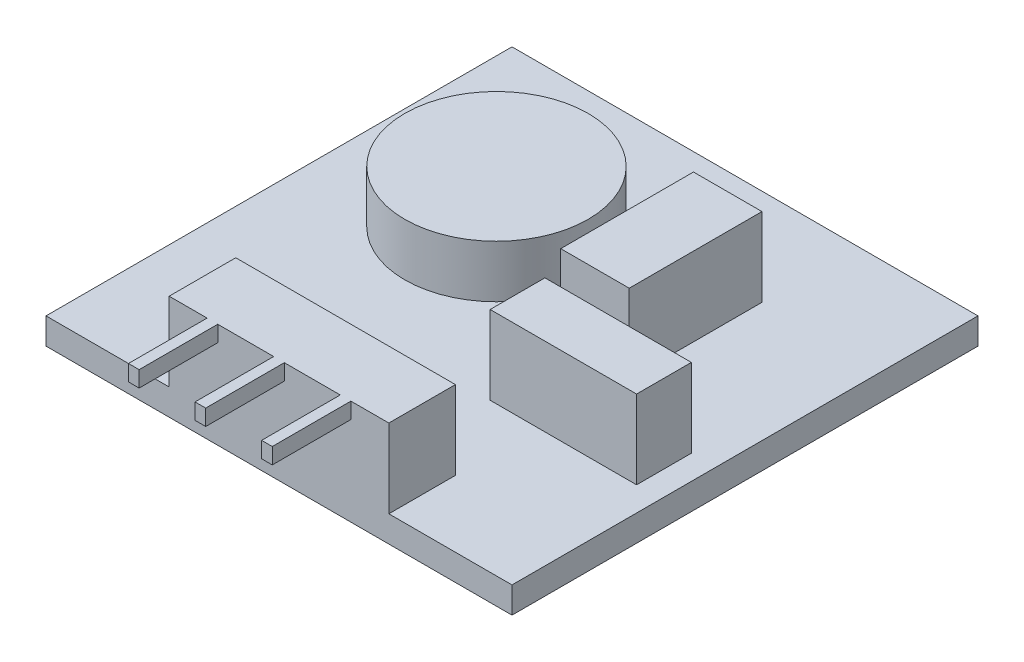
SolidWorks part; units mm, degrees
ref_plane "Front Plane" through (0, 0, 0) normal (0, 0, 1) x (1, 0, 0)
ref_plane "Top Plane" through (0, 0, 0) normal (0, 1, 0) x (1, 0, 0)
ref_plane "Right Plane" through (0, 0, 0) normal (1, 0, 0) x (0, 0, -1)
sketch "Sketch1" plane through (0, 0, 0) normal (0, 1, 0) x (1, 0, 0)
  line L1 (-8.89, -8.89) -> (8.89, -8.89)
  line L2 (-8.89, -8.89) -> (-8.89, 8.89)
  line L3 (-8.89, 8.89) -> (8.89, 8.89)
  line L4 (8.89, -8.89) -> (8.89, 8.89)
  line L5 (-8.89, -8.89) -> (8.89, 8.89) construction
  line L6 (-8.89, 8.89) -> (8.89, -8.89) construction
  point P0 (0, 0)
  dimension "D1" = 17.78
extrude "Boss-Extrude1" add sketch "Sketch1" along normal blind 1
sketch "Sketch2" plane through (0, 1, 0) normal (0, 1, 0) x (1, 0, 0)
  circle A0 centre (-3.2361, 2.6432) radius 3.5
  dimension "D1" = 7
extrude "Boss-Extrude2" add sketch "Sketch2" along normal blind 2
sketch "Sketch3" plane through (0, 1, 0) normal (0, 1, 0) x (1, 0, 0)
  line L1 (2.3718, -1.1156) -> (7.9596, -1.1156)
  line L2 (2.3718, -1.1156) -> (2.3718, -3.206)
  line L3 (2.3718, -3.206) -> (7.9596, -3.206)
  line L4 (7.9596, -1.1156) -> (7.9596, -3.206)
  line L5 (2.3718, -1.1156) -> (7.9596, -3.206) construction
  line L6 (2.3718, -3.206) -> (7.9596, -1.1156) construction
  line L7 (1.7085, 0.1508) -> (4.3215, 0.1508)
  line L8 (1.7085, 0.1508) -> (1.7085, 5.216)
  line L9 (1.7085, 5.216) -> (4.3215, 5.216)
  line L10 (4.3215, 0.1508) -> (4.3215, 5.216)
  line L11 (1.7085, 0.1508) -> (4.3215, 5.216) construction
  line L12 (1.7085, 5.216) -> (4.3215, 0.1508) construction
  point P0 (5.1657, -2.1608)
  point P5 (3.015, 2.6834)
extrude "Boss-Extrude3" add sketch "Sketch3" along normal blind 3 contours L10 L9 L8 L7
sketch "Sketch4" plane through (0, 1, 0) normal (0, 1, 0) x (1, 0, 0)
  line L0 (-8.89, -8.89) -> (8.89, -8.89) construction
  line L1 (-4.191, -6.35) -> (4.191, -6.35)
  line L2 (-4.191, -6.35) -> (-4.191, -8.89)
  line L3 (-4.191, -8.89) -> (4.191, -8.89)
  line L4 (4.191, -6.35) -> (4.191, -8.89)
  line L5 (-4.191, -6.35) -> (4.191, -8.89) construction
  line L6 (-4.191, -8.89) -> (4.191, -6.35) construction
  line L7 (0, 0) -> (0, -7.62) construction
  point P0 (0, -7.62)
  dimension "D1" = 8.382
  dimension "D2" = 2.54
extrude "Boss-Extrude4" add sketch "Sketch4" along normal blind 3
sketch "Sketch5" plane through (0, 0, 8.89) normal (0, 0, 1) x (1, 0, 0)
  line L0 (-2.54, 3.6952) -> (0, 3.6952) construction
  line L1 (-2.7432, 4) -> (-2.3368, 4)
  line L2 (-2.7432, 4) -> (-2.7432, 3.3904)
  line L3 (-2.7432, 3.3904) -> (-2.3368, 3.3904)
  line L4 (-2.3368, 4) -> (-2.3368, 3.3904)
  line L5 (-2.7432, 4) -> (-2.3368, 3.3904) construction
  line L6 (-2.7432, 3.3904) -> (-2.3368, 4) construction
  line L7 (-0.2032, 4) -> (0.2032, 4)
  line L8 (-0.2032, 4) -> (-0.2032, 3.3904)
  line L9 (-0.2032, 3.3904) -> (0.2032, 3.3904)
  line L10 (0.2032, 4) -> (0.2032, 3.3904)
  line L11 (-0.2032, 4) -> (0.2032, 3.3904) construction
  line L12 (-0.2032, 3.3904) -> (0.2032, 4) construction
  line L13 (2.3368, 4) -> (2.7432, 4)
  line L14 (2.3368, 4) -> (2.3368, 3.3904)
  line L15 (2.3368, 3.3904) -> (2.7432, 3.3904)
  line L16 (2.7432, 4) -> (2.7432, 3.3904)
  line L17 (2.3368, 4) -> (2.7432, 3.3904) construction
  line L18 (2.3368, 3.3904) -> (2.7432, 4) construction
  line L19 (0, 3.6952) -> (2.54, 3.6952) construction
  line L20 (2.54, 3.6952) -> (4.191, 3.6952) construction
  line L21 (4.191, 4) -> (4.191, 1) construction
  line L22 (-2.54, 3.6952) -> (-4.191, 3.6952) construction
  line L24 (-4.191, 4) -> (-4.191, 1) construction
  line L25 (-4.191, 4) -> (4.191, 4) construction
  point P0 (-2.54, 3.6952)
  point P5 (0, 3.6952)
  point P10 (2.54, 3.6952)
  dimension "D1" = 0.4064
  dimension "D2" = 0.6096
  dimension "D3" = 2.54
extrude "Boss-Extrude5" add sketch "Sketch5" along normal blind 3 contours L3 L4 L1 L2
